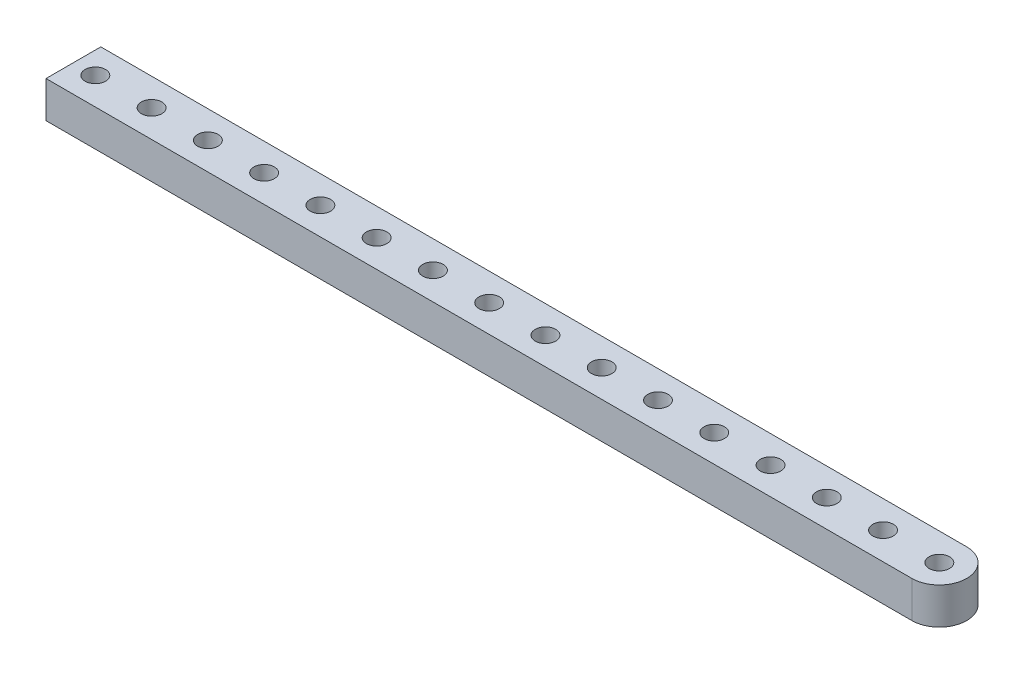
SolidWorks part; units mm, degrees
ref_plane "Front Plane" through (0, 0, 0) normal (0, 0, 1) x (1, 0, 0)
ref_plane "Top Plane" through (0, 0, 0) normal (0, 1, 0) x (1, 0, 0)
ref_plane "Right Plane" through (0, 0, 0) normal (1, 0, 0) x (0, 0, -1)
ref_plane "Plane1" through (0, 6.35, 0) normal (0, 1, 0) x (1, 0, 0)
sketch "Sketch1" plane through (0, 6.35, 0) normal (0, 1, 0) x (1, 0, 0)
  line L0 (78.232, 4.7625) -> (-78.232, 4.7625)
  line L1 (-78.232, -4.7625) -> (78.232, -4.7625)
  arc A0 (78.232, -4.7625) -> (78.232, 4.7625) centre (78.232, 0) ccw
  arc A1 (-78.232, 4.7625) -> (-78.232, -4.7625) centre (-78.232, 0) ccw
  circle A2 centre (78.232, 0) radius 1.778
  circle A3 centre (68.453, 0) radius 1.778
  circle A4 centre (58.674, 0) radius 1.778
  circle A5 centre (48.895, 0) radius 1.778
  circle A6 centre (39.116, 0) radius 1.778
  circle A7 centre (29.337, 0) radius 1.778
  circle A8 centre (19.558, 0) radius 1.778
  circle A9 centre (9.779, 0) radius 1.778
  circle A10 centre (0, 0) radius 1.778
  circle A11 centre (-9.779, 0) radius 1.778
  circle A12 centre (-19.558, 0) radius 1.778
  circle A13 centre (-29.337, 0) radius 1.778
  circle A14 centre (-39.116, 0) radius 1.778
  circle A15 centre (-48.895, 0) radius 1.778
  circle A16 centre (-58.674, 0) radius 1.778
  circle A17 centre (-68.453, 0) radius 1.778
  circle A18 centre (-78.232, 0) radius 1.778
extrude "Boss-Extrude1" add sketch "Sketch1" against normal blind 6.35
sketch "Sketch2" plane through (0, 6.35, 0) normal (0, 1, 0) x (1, 0, 0)
  line L0 (-78.232, -4.7625) -> (78.232, -4.7625) construction
  line L1 (-83.0214, 5.08) -> (-72.263, 5.08)
  line L2 (-83.0214, 5.08) -> (-83.0214, -4.7625)
  line L3 (-83.0214, -4.7625) -> (-72.263, -4.7625)
  line L4 (-72.263, 5.08) -> (-72.263, -4.7625)
  circle A1 centre (-68.453, 0) radius 1.778 construction
  dimension "D1" = 9.8425
  dimension "D2" = 3.81
extrude "Cut-Extrude1" cut sketch "Sketch2" against normal through all
